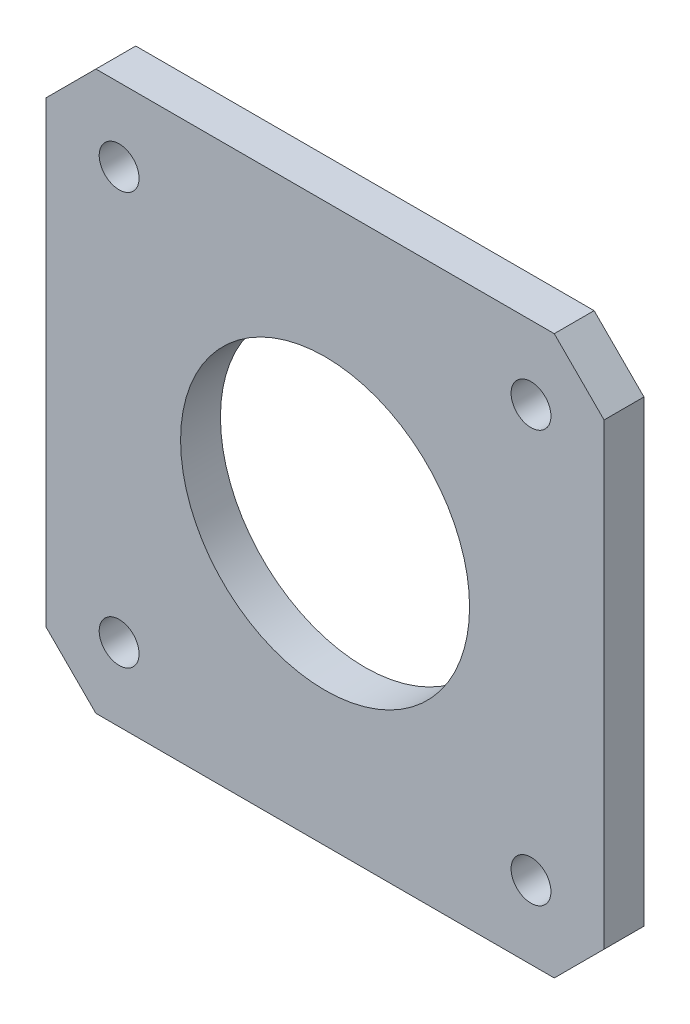
SolidWorks part; units mm, degrees
ref_plane "Спереди" through (0, 0, 0) normal (0, 0, 1) x (1, 0, 0)
ref_plane "Сверху" through (0, 0, 0) normal (0, 1, 0) x (1, 0, 0)
ref_plane "Справа" through (0, 0, 0) normal (1, 0, 0) x (0, 0, -1)
sketch "Эскиз1" plane through (0, 0, 0) normal (0, 0, 1) x (1, 0, 0)
  line L0 (17.25, 21) -> (21, 17.25)
  line L1 (-17.25, -21) -> (17.25, -21)
  line L2 (-21, -17.25) -> (-21, 17.25)
  line L3 (-17.25, 21) -> (17.25, 21)
  line L4 (21, -17.25) -> (21, 17.25)
  line L5 (-21, -21) -> (21, 21) construction
  line L6 (-21, 21) -> (21, -21) construction
  line L7 (-21, 17.25) -> (-17.25, 21)
  line L8 (17.25, -21) -> (21, -17.25)
  line L9 (-21, -17.25) -> (-17.25, -21)
  circle A0 centre (-15.5, 15.5) radius 1.5
  circle A1 centre (15.5, 15.5) radius 1.5
  circle A2 centre (15.5, -15.5) radius 1.5
  circle A3 centre (-15.5, -15.5) radius 1.5
  circle A4 centre (0, 0) radius 10.875
  point P0 (0, 0)
  point P17 (0, 0)
  dimension "D2" = 3
  dimension "D5" = 21.75
  dimension "D1" = 42
  dimension "D3" = 15.5
  dimension "D4" = 4
extrude "Бобышка-Вытянуть1" add sketch "Эскиз1" along normal blind 3
